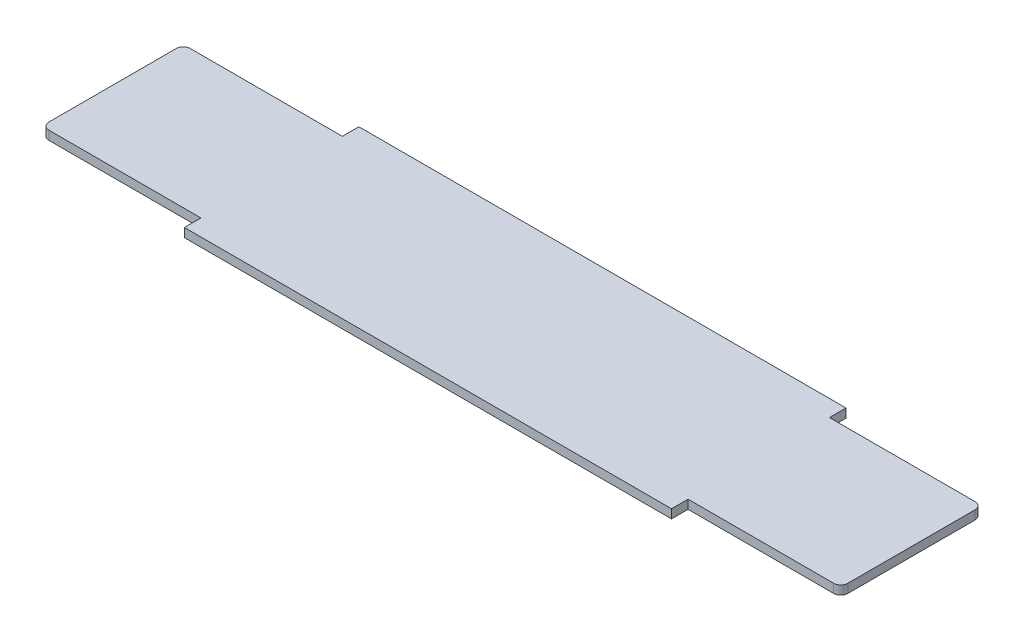
SolidWorks part; units mm, degrees
ref_plane "Front Plane" through (0, 0, 0) normal (0, 0, 1) x (1, 0, 0)
ref_plane "Top Plane" through (0, 0, 0) normal (0, 1, 0) x (1, 0, 0)
ref_plane "Right Plane" through (0, 0, 0) normal (1, 0, 0) x (0, 0, -1)
sketch "Sketch1" plane through (0, 0, 0) normal (0, 1, 0) x (1, 0, 0)
  line L1 (0, 0) -> (-287.02, 0)
  line L2 (0, 0) -> (0, 50.8)
  line L3 (0, 50.8) -> (-287.02, 50.8)
  line L4 (-287.02, 0) -> (-287.02, 50.8)
  dimension "D1" = 287.02
  dimension "D2" = 50.8
extrude "Boss-Extrude1" add sketch "Sketch1" along normal blind 3.175
sketch "Sketch2" plane through (0, 3.175, 0) normal (0, 1, 0) x (1, 0, 0)
  line L0 (-229.87, 50.8) -> (-229.87, 0) construction
  line L1 (0, 50.8) -> (-287.02, 50.8) construction
  line L2 (-287.02, 0) -> (0, 0) construction
  line L3 (-287.02, 50.8) -> (-287.02, 0) construction
  line L4 (-287.02, 25.4) -> (-229.87, 25.4) construction
  line L5 (-54.864, 0) -> (-54.864, -5.9436)
  line L6 (-229.87, 50.8) -> (-54.864, 50.8)
  line L7 (-229.87, 50.8) -> (-229.87, 56.7436)
  line L8 (-229.87, 56.7436) -> (-54.864, 56.7436)
  line L9 (-54.864, 50.8) -> (-54.864, 56.7436)
  line L10 (-229.87, -5.9436) -> (-54.864, -5.9436)
  line L11 (-229.87, 0) -> (-229.87, -5.9436)
  line L12 (-229.87, 0) -> (-54.864, 0)
  dimension "D1" = 57.15
  dimension "D2" = 5.9436
  dimension "D3" = 175.006
extrude "Boss-Extrude2" add sketch "Sketch2" against normal up to surface (3.175 mm away) up to face at (-143.51, 0, -25.4)
fillet "Fillet1" radius 2.54 2 edges at (0, 1.5875, -50.8) (0, 1.5875, 0)
fillet "Fillet2" radius 2.54 2 edges at (-287.02, 1.5875, 0) (-287.02, 1.5875, -50.8)
